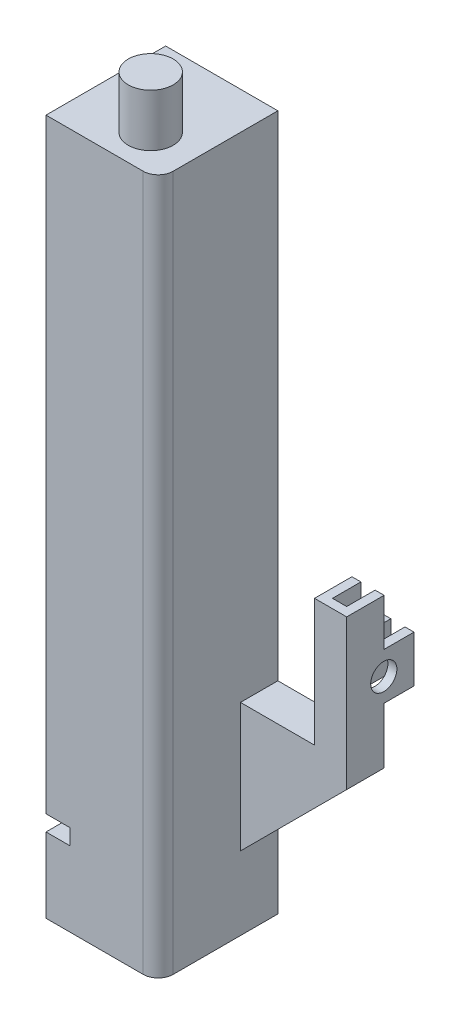
SolidWorks part; units mm, degrees
ref_plane "Front Plane" through (0, 0, 0) normal (0, 0, 1) x (1, 0, 0)
ref_plane "Top Plane" through (0, 0, 0) normal (0, 1, 0) x (1, 0, 0)
ref_plane "Right Plane" through (0, 0, 0) normal (1, 0, 0) x (0, 0, -1)
sketch "Sketch1" plane through (0, 0, 0) normal (0, 1, 0) x (1, 0, 0)
  line L0 (-68.486, 0) -> (57.6746, 0) construction
  line L1 (0, 62.7099) -> (0, -58.019) construction
  line L3 (-7.5, -7.5) -> (7.5, -7.5)
  line L4 (-7.5, -7.5) -> (-7.5, 7.5)
  line L5 (-7.5, 7.5) -> (7.5, 7.5)
  line L6 (7.5, -7.5) -> (7.5, 7.5)
  line L7 (-7.5, -7.5) -> (7.5, 7.5) construction
  line L8 (-7.5, 7.5) -> (7.5, -7.5) construction
  point P5 (0, 0)
  dimension "D1" = 15
  dimension "D2" = 15
extrude "Boss-Extrude1" add sketch "Sketch1" along normal blind 93
sketch "Sketch2" plane through (0, 93, 0) normal (0, 1, 0) x (1, 0, 0)
  line L0 (7.5, -7.5) -> (7.5, 7.5) construction
  line L1 (-7.5, -7.5) -> (7.5, -7.5) construction
  circle A0 centre (1.5, -2.5) radius 3
  dimension "D1" = 6
  dimension "D2" = 6
  dimension "D3" = 5
extrude "Boss-Extrude2" add sketch "Sketch2" along normal blind 7
fillet "Fillet1" radius 2 1 edges at (7.5, 46.5, 7.5)
sketch "Sketch5" plane through (0, 0, -7.5) normal (0, 0, -1) x (-1, 0, 0)
  line L0 (-28.1963, 0) -> (9.6095, 0) construction
  line L1 (-7.5, 24) -> (-7.5, 27)
  line L2 (-7.5, 93) -> (-7.5, 0) construction
  line L3 (-7.5, 27) -> (-20.5, 27)
  line L4 (-20.5, 27) -> (-20.5, 44)
  line L5 (-20.5, 44) -> (-21.7, 44)
  line L6 (-21.7, 44) -> (-21.7, 24)
  line L7 (-21.7, 24) -> (-7.5, 24)
  line L9 (-18.6, 27) -> (-18.6, 44)
  line L10 (-18.6, 44) -> (-17.4, 44)
  line L11 (-17.4, 44) -> (-17.4, 27)
  point P8 (-28.1963, 0)
  point P13 (0, 0)
  point P16 (0, 0)
  point P19 (0, 0)
  line M8 (-7.5, 93) -> (-7.5, 0)
  dimension "D1" = 3
  dimension "D2" = 14.2
  dimension "D3" = 1.2
  dimension "D4" = 20
  dimension "D5" = 1.9
  dimension "D6" = 24
extrude "Boss-Extrude3" add sketch "Sketch5" against normal blind 4 and the other way blind 1 contours L6 L7 L3 L4 L5 M8 | L11 L10 L9 L3
sketch "Sketch6" plane through (0, 0, -3.5) normal (0, 0, 1) x (1, 0, 0)
  line L0 (21.7, 44) -> (21.7, 24) construction
  line L1 (17.4, 24) -> (21.7, 24)
  line L2 (17.4, 24) -> (17.4, 44)
  line L3 (17.4, 44) -> (21.7, 44)
  line L4 (21.7, 24) -> (21.7, 44)
  line L5 (17.4, 24) -> (21.7, 44) construction
  line L6 (17.4, 44) -> (21.7, 24) construction
  line L7 (18.6, 44) -> (17.4, 44) construction
  line L8 (17.4, 44) -> (17.4, 27) construction
  line L10 (21.7, 24) -> (7.5, 24) construction
  point P0 (19.55, 34)
extrude "Boss-Extrude4" add sketch "Sketch6" against normal blind 1.2
sketch "Sketch7" plane through (21.7, 0, 0) normal (1, 0, 0) x (0, 0, -1)
  line L0 (5.5, 34.5) -> (5.5, 44)
  line L1 (8.5, 44) -> (8.5, 24) construction
  line L2 (5.5, 44) -> (8.5, 44)
  line L3 (8.5, 44) -> (8.5, 37.74)
  line L4 (8.5, 37.74) -> (12.5, 37.74)
  line L5 (12.5, 37.74) -> (12.5, 31.5)
  line L6 (12.5, 31.5) -> (8.5, 31.5)
  line L8 (8.5, 31.5) -> (5.5, 34.5)
  line L11 (8.5, 24) -> (3.5, 24) construction
  point P2 (0, 0)
  point P3 (0, 0)
  point P4 (0, 0)
  point P7 (9.5, 10)
  point P13 (0, 0)
  point P14 (0, 0)
  point P15 (0, 0)
  dimension "D1" = 6.24
  dimension "D2" = 4
  dimension "D3" = 7.5
  dimension "D4" = 3
  dimension "D5" = 3
  dimension "D6" = 12.5
extrude "Boss-Extrude5" add sketch "Sketch7" against normal up to surface (4.3 mm away) up to face at (17.4, 35.5, -6)
sketch "Sketch9" plane through (0, 44, 0) normal (0, 1, 0) x (1, 0, 0)
  line L0 (18.6, 4.7) -> (20.5, 4.7)
  line L1 (20.5, 4.7) -> (20.5, 24.7)
  line L2 (20.5, 24.7) -> (18.6, 24.7)
  line L3 (18.6, 24.7) -> (18.6, 4.7)
  dimension "D1" = 20
extrude "Cut-Extrude2" cut sketch "Sketch9" against normal up to surface (17 mm away) up to face at (19.55, 27, -6.6)
sketch "Sketch10" plane through (21.7, 0, 0) normal (1, 0, 0) x (0, 0, -1)
  line L0 (12.5, 31.5) -> (12.5, 37.74) construction
  line L1 (12.5, 37.74) -> (8.5, 37.74) construction
  circle A0 centre (8.46, 34.62) radius 1.75
  dimension "D1" = 3.5
  dimension "D2" = 4.04
  dimension "D3" = 3.12
extrude "Cut-Extrude3" cut sketch "Sketch10" against normal blind 10
sketch "Sketch11" plane through (7.5, 0, 0) normal (-1, 0, 0) x (0, 0, 1)
  line L12 (-7.5, 24) -> (-7.5, 27)
  line L13 (-7.5, 27) -> (-8.5, 27)
  line L14 (-8.5, 27) -> (-8.5, 24)
  line L15 (-8.5, 24) -> (-7.5, 24)
  line L16 (-7.5, 24) -> (-7.5, 27)
  line L17 (-7.5, 27) -> (-8.5, 27)
  line L18 (-8.5, 27) -> (-8.5, 24)
  line L20 (-8.5, 24) -> (-7.5, 24)
  dimension "D1" = 0
extrude "Boss-Extrude6" add sketch "Sketch11" along normal up to surface (15 mm away) up to face at (-7.5, 46.5, 0)
sketch "Sketch12" plane through (0, 27, 0) normal (0, 1, 0) x (1, 0, 0)
  line L0 (-7.5, 8.5) -> (-7.5, 7.5)
  line L1 (-7.5, 7.5) -> (7.5, 7.5)
  line L2 (7.5, 7.5) -> (7.5, 8.5)
  line L3 (-7.5, 8.5) -> (17.4, 8.5) construction
  line L4 (7.5, 8.5) -> (-7.5, 8.5)
extrude "Boss-Extrude7" add sketch "Sketch12" along normal up to surface and the other way up to surface up to face at (1.5, 93, -0.5) other way up to face at (1.1828, 0, 1.1828)
sketch "Sketch3" plane through (0, 0, 7.5) normal (0, 0, 1) x (1, 0, 0)
  line L0 (-7.5, 12.1) -> (-4.3, 12.1)
  line L1 (-7.5, 93) -> (-7.5, 0) construction
  line L2 (-4.3, 12.1) -> (-4.3, 10)
  line L3 (-4.3, 10) -> (-7.5, 10)
  line L4 (-7.5, 10) -> (-7.5, 12.1)
  dimension "D1" = 10
  dimension "D2" = 2.1
  dimension "D3" = 3.2
extrude "Cut-Extrude1" cut sketch "Sketch3" against normal through all
sketch "Sketch13" plane through (0, 0, -3.5) normal (0, 0, 1) x (1, 0, 0)
  line L0 (21.7, 24) -> (7.5, 24)
  line L1 (7.5, 24) -> (7.5, 9.8)
  line L2 (7.5, 93) -> (7.5, 0) construction
  line L3 (7.5, 9.8) -> (21.7, 24)
  dimension "D1" = 45
extrude "Boss-Extrude8" add sketch "Sketch13" against normal up to surface (5 mm away) up to face at (8.2111, 28.4556, -8.5)
